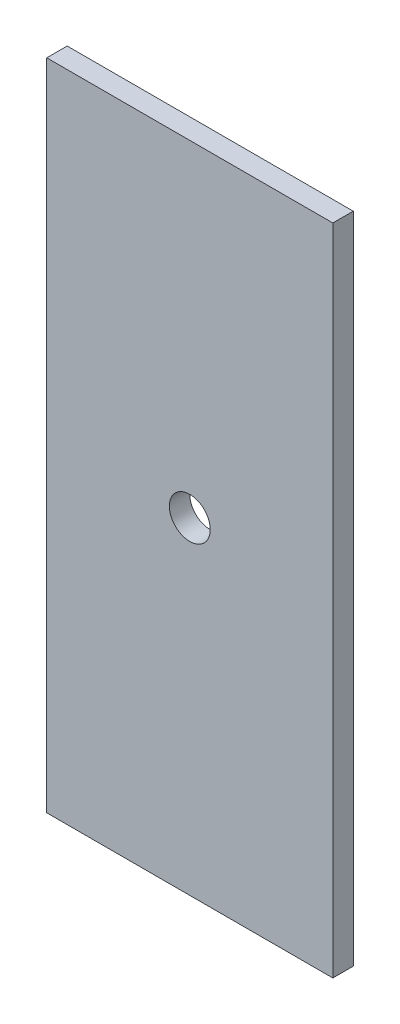
SolidWorks part; units mm, degrees
material "Pine"
ref_plane "Front Plane" through (0, 0, 0) normal (0, 0, 1) x (1, 0, 0)
ref_plane "Top Plane" through (0, 0, 0) normal (0, 1, 0) x (1, 0, 0)
ref_plane "Right Plane" through (0, 0, 0) normal (1, 0, 0) x (0, 0, -1)
sketch "Sketch1" plane through (0, 0, 0) normal (0, 0, 1) x (1, 0, 0)
  line L1 (-44.45, -101.6) -> (44.45, -101.6)
  line L2 (-44.45, -101.6) -> (-44.45, 101.6)
  line L3 (-44.45, 101.6) -> (44.45, 101.6)
  line L4 (44.45, -101.6) -> (44.45, 101.6)
  line L5 (-44.45, -101.6) -> (44.45, 101.6) construction
  line L6 (-44.45, 101.6) -> (44.45, -101.6) construction
  point P0 (0, 0)
  dimension "D1" = 88.9
  dimension "D2" = 203.2
extrude "Boss-Extrude1" add sketch "Sketch1" along normal mid plane 6.35 contours L3 L4 L1 L2
hole_wizard "1/2 (0.5) Diameter Hole1" positions "3DSketch1" profile "Sketch3" hole size "1/2" standard "ANSI Inch" end condition through all
sketch3d "3DSketch1"
  line L0 (0, -101.6, 3.175) -> (0, 101.6, 3.175)
  line L1 (-44.45, -101.6, 3.175) -> (44.45, -101.6, 3.175) construction
  line L2 (-44.45, 101.6, 3.175) -> (44.45, 101.6, 3.175) construction
  point P2 (0, 0, 3.175)
sketch "Sketch3" plane through (0, 0, 3.175) normal (1, 0, 0) x (0, -1, 0)
  line L0 (0, 0) -> (0, 6.35)
  line L1 (0, 6.35) -> (6.35, 6.35)
  line L2 (6.35, 6.35) -> (6.35, 0)
  line L5 (6.35, 0) -> (0, 0)
  line L11 (0, -6.35) -> (0, 107.95) construction
  dimension "Thru Hole Dia." = 12.7
  dimension "Thru Hole Depth" = 6.35
